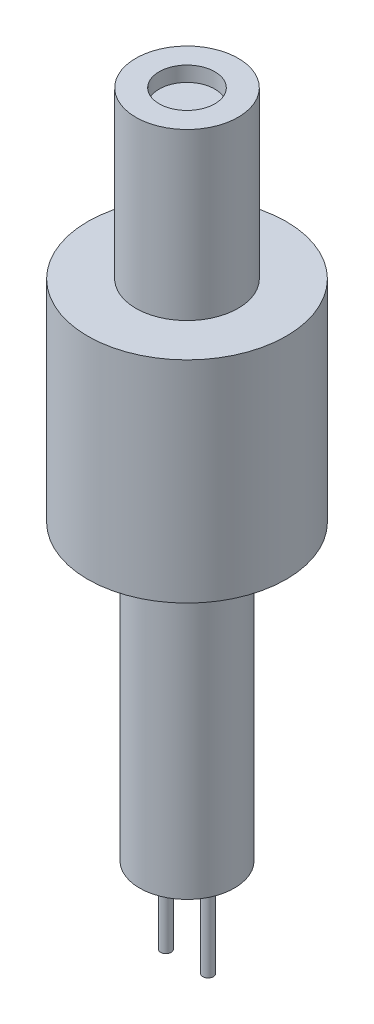
SolidWorks part; units mm, degrees
material "Custom Plastic"
ref_plane "Front Plane" through (0, 0, 0) normal (0, 0, 1) x (1, 0, 0)
ref_plane "Top Plane" through (0, 0, 0) normal (0, 1, 0) x (1, 0, 0)
ref_plane "Right Plane" through (0, 0, 0) normal (1, 0, 0) x (0, 0, -1)
sketch "Sketch1" plane through (0, 0, 0) normal (0, 1, 0) x (1, 0, 0)
  circle A0 centre (0, 0) radius 3.15
  dimension "D1" = 6.3
extrude "Boss-Extrude1" add sketch "Sketch1" along normal blind 19.5
sketch "Sketch2" plane through (0, 0, 0) normal (0, -1, 0) x (1, 0, 0)
  line L0 (-3.15, 0) -> (3.15, 0) construction
  circle A0 centre (0, 0) radius 3.15 construction
  circle A1 centre (-1.4, 0) radius 0.35
  circle A2 centre (1.4, 0) radius 0.35
  point P7 (0, 0)
  dimension "D1" = 0.7
  dimension "D2" = 2.8
  dimension "D3" = 1.4
extrude "Boss-Extrude2" add sketch "Sketch2" along normal blind 5.8
sketch "Sketch3" plane through (0, 19.5, 0) normal (0, 1, 0) x (1, 0, 0)
  circle A0 centre (0, 0) radius 6.6
  dimension "D1" = 13.2
extrude "Boss-Extrude3" add sketch "Sketch3" along normal blind 14
sketch "Sketch4" plane through (0, 33.5, 0) normal (0, 1, 0) x (1, 0, 0)
  circle A0 centre (0, 0) radius 3.4
  dimension "D1" = 6.8
extrude "Boss-Extrude4" add sketch "Sketch4" along normal blind 11
sketch "Sketch5" plane through (0, 44.5, 0) normal (0, 1, 0) x (1, 0, 0)
  circle A0 centre (0, 0) radius 1.85
  dimension "D1" = 3.7
extrude "Cut-Extrude1" cut sketch "Sketch5" against normal blind 1
